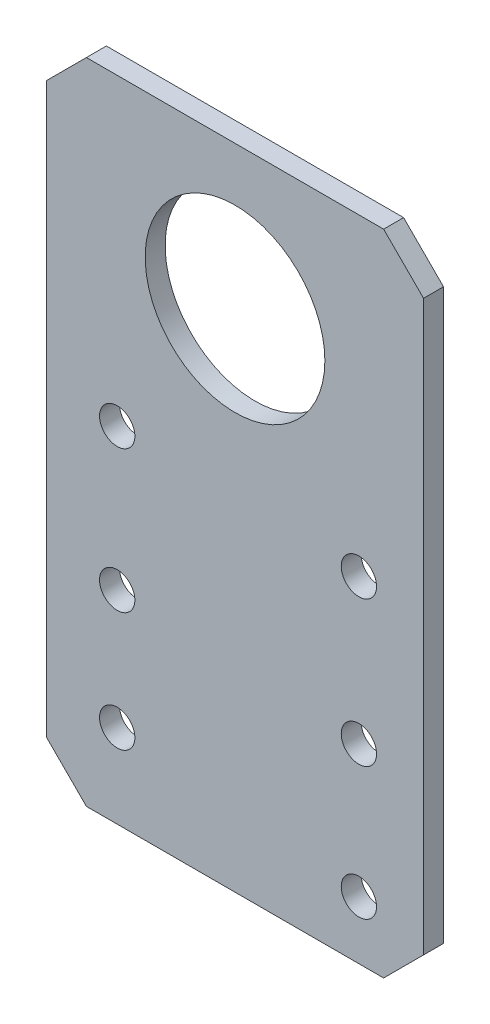
SolidWorks part; units mm, degrees
ref_plane "Front Plane" through (0, 0, 0) normal (0, 0, 1) x (1, 0, 0)
ref_plane "Top Plane" through (0, 0, 0) normal (0, 1, 0) x (1, 0, 0)
ref_plane "Right Plane" through (0, 0, 0) normal (1, 0, 0) x (0, 0, -1)
sketch "Sketch1" plane through (0, 0, 0) normal (0, 0, 1) x (1, 0, 0)
  line L0 (293.8696, 131.6712) -> (293.8696, 28.5482)
  line L1 (263.8892, 131.6712) -> (323.85, 131.6712)
  line L2 (263.8892, 131.6712) -> (263.8892, 28.5482)
  line L3 (263.8892, 28.5482) -> (323.85, 28.5482)
  line L4 (323.85, 25.4) -> (323.85, 76.2)
  line L5 (323.85, 76.2) -> (-323.85, 76.2)
  line L6 (-323.85, 76.2) -> (-323.85, 25.4)
  line L7 (-323.85, 25.4) -> (323.85, 25.4)
  line L8 (323.85, 25.4) -> (323.85, 76.2) construction
  line L9 (323.85, 76.2) -> (-323.85, 76.2) construction
  line L10 (-323.85, 76.2) -> (-323.85, 25.4) construction
  line L11 (-323.85, 25.4) -> (323.85, 25.4) construction
  line L12 (323.85, 131.6712) -> (323.85, 28.5482)
  arc A0 (294.051, 95.5845) -> (293.6882, 122.1719) centre (293.8696, 108.8782) ccw construction
  arc A1 (294.051, 95.5845) -> (293.6882, 122.1719) centre (293.8696, 108.8782) ccw construction
  circle A2 centre (293.8696, 108.8782) radius 14.2875
  dimension "D2" = 28.575
  dimension "D1" = 0
extrude "Boss-Extrude1" add sketch "Sketch1" along normal blind 3.175 contours A2 L0 L1 L2 L3 | A2 L0 L3 L12 L1
chamfer "Chamfer1" distance 6.35 angle 45 4 edges at (263.8892, 28.5482, 1.5875) (323.85, 28.5482, 1.5875) (323.85, 131.6712, 1.5875) (263.8892, 131.6712, 1.5875)
hole_wizard "#10 Clearance Hole1" positions "Sketch2" profile "Sketch3" hole size "#10" standard "ANSI Inch"
sketch "Sketch2" plane through (0, 0, 0) normal (0, 0, 1) x (1, 0, 0)
  point P0 (275.1368, 83.3634)
  point P2 (275.1368, 60.7934)
  point P4 (313.5658, 58.8264)
  point P6 (313.5658, 81.8856)
  point P9 (275.1368, 41.8476)
  point P11 (313.5658, 37.7867)
sketch "Sketch3" plane through (275.1368, 83.3634, 0) normal (1, 0, 0) x (0, 1, 0)
  line L0 (0, 0) -> (0, 4.8604)
  line L1 (0, 4.8604) -> (2.8067, 3.174)
  line L2 (2.8067, 3.174) -> (2.8067, 0)
  line L5 (2.8067, 0) -> (0, 0)
  line L10 (0, 4.8604) -> (-2.8067, 3.174) construction
  line L11 (0, -6.35) -> (0, 107.95) construction
  dimension "Hole Dia." = 5.6134
  dimension "Hole Depth" = 3.174
  dimension "Drill Angle" = 118
